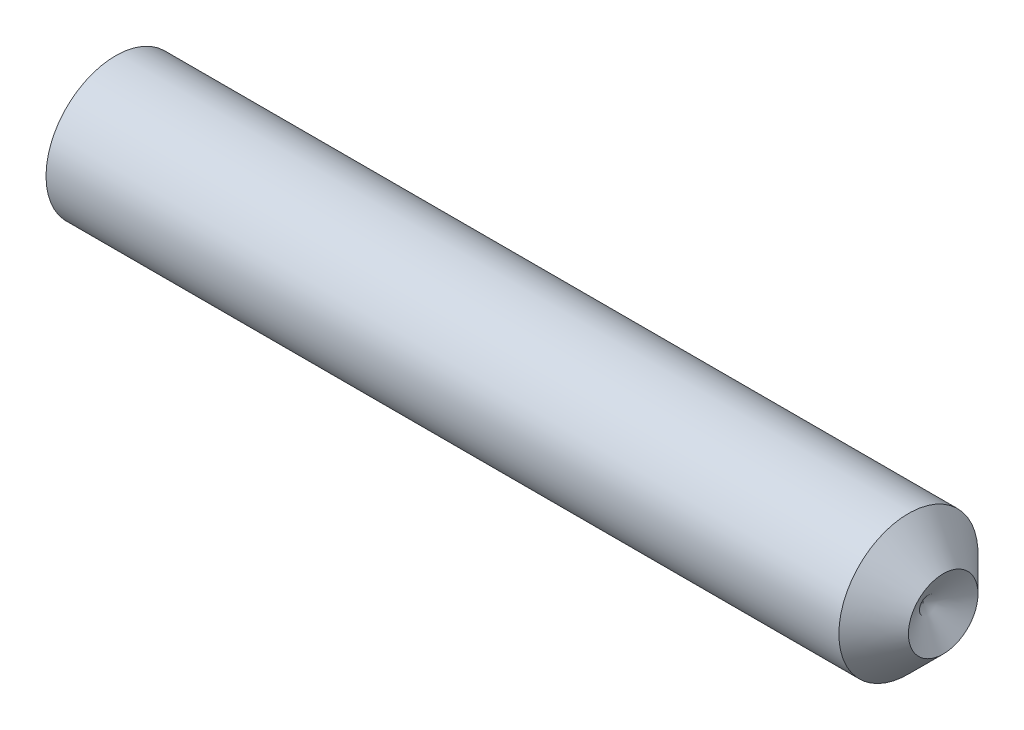
SolidWorks part; units mm, degrees
revolve "BaseBody" add sketch "BodySke" angle 360 about L5
sketch "BodySke" plane through (0, 0, 0) normal (0, 0, 1) x (1, 0, 0)
  line L0 (0, 0) -> (0, 2.055)
  line L1 (0, 2.055) -> (0.2569, 2.5)
  line L2 (0.2569, 2.5) -> (28.75, 2.5)
  line L3 (28.75, 2.5) -> (30, 1.25)
  line L4 (29.2783, 0) -> (0, 0)
  line L5 (-12.7, 0) -> (88.9, 0) construction
  line L6 (29.2783, 0) -> (30, 1.25)
  line L7 (30, 1.25) -> (30, 10.775) construction
  line L8 (0, -2.055) -> (0.2569, -2.5) construction
  line L9 (29.2783, 0) -> (30, -1.25) construction
  line L10 (28.75, -2.5) -> (30, -1.25) construction
  line L11 (0.4, 15.875) -> (0.4, -3.175) construction
  dimension "Diameter" = 5
  dimension "Drive_ch_ang" = 60
  dimension "Minor_dia" = 4.11
  dimension "Cup_ang" = 120
  dimension "Cup_dia" = 2.5
  dimension "Cup_nose_ang" = 45
  dimension "Advance" = 0.8
cosmetic thread "ThreadCosmetic" parameters "Thread_minor"=4.11
ref_plane "Plane1" through (0, 0, 0) normal (0, 0, 1) x (1, 0, 0)
ref_plane "Plane2" through (0, 0, 0) normal (0, 1, 0) x (1, 0, 0)
ref_plane "Plane3" through (0, 0, 0) normal (1, 0, 0) x (0, 0, -1)
sketch "Sketch2" plane through (0, 0, 0) normal (-1, 0, 0) x (0, 0, 1)
  line L0 (0.7217, 1.25) -> (-0.7217, 1.25)
  line L1 (-0.7217, 1.25) -> (-1.4434, 0)
  line L2 (0.7217, 1.25) -> (1.4434, 0)
  line L3 (0.7217, -1.25) -> (1.4434, 0)
  line L4 (0.7217, -1.25) -> (-0.7217, -1.25)
  line L5 (-0.7217, -1.25) -> (-1.4434, 0)
  dimension "Hex_size" = 2.5
  dimension "D2" = 1.25
  dimension "D3" = 1.25
extrude "Hex" cut sketch "Sketch2" against normal blind 2
sketch "ThdSchSke" plane through (0, 0, 0) normal (0, 0, 1) x (1, 0, 0)
  line L0 (0.2569, -2.055) -> (-0.0547, -2.5)
  line L1 (0.2569, -2.055) -> (0.5685, -2.5)
  line L2 (0.5685, -2.5) -> (0.5685, -3.125)
  line L3 (-3.175, 0) -> (5.1513, 0) construction
  line L4 (0.2569, 2.5) -> (0.2569, -2.5) construction
  line L5 (0.5685, -3.125) -> (-0.0547, -3.125)
  line L6 (-0.0547, -3.125) -> (-0.0547, -2.5)
  dimension "Thread_minor" = 4.11
  dimension "Diameter" = 5
revolve "ThreadSchematic" [suppressed] cut sketch "ThdSchSke" angle 360 about L3
pattern_linear "ThdSchPat" [suppressed]
equation "\"D2@Sketch2\" = \"Hex_size@Sketch2\" / 2"
equation "\"D3@Sketch2\" = \"Hex_size@Sketch2\" / 2"
equation "\"Thread_minor@ThreadCosmetic\" = \"Minor_dia@BodySke\""
equation "\"Thread_minor@ThdSchSke\" = \"Thread_minor@ThreadCosmetic\""
equation "\"Diameter@ThdSchSke\" = \"Diameter@BodySke\""
equation "\"Overcut@ThdSchSke\" = \"Diameter@BodySke\" * 1.25"
equation "\"Num_threads@ThdSchPat\" = int( (\"Length@BodySke\" - ( ( ( \"Diameter@BodySke\" - \"Minor_dia@BodySke\" ) * 0.5 ) / tan( \"Drive_ch_ang@BodySke\" * 0.017453292 ) ) - ( ( ( \"Diameter@BodySke\" - \"Cup_dia@BodySke\" ) * 0.5 ) * tan( \"Cup_nose_ang@BodySke\" * 0.017453292 ) ) ) / \"Advance@BodySke\" + 0.999 )  + 1"
equation "\"Advance@ThdSchPat\" = (\"Length@BodySke\" - ( ( ( \"Diameter@BodySke\" - \"Minor_dia@BodySke\" ) * 0.5 ) / tan( \"Drive_ch_ang@BodySke\" * 0.017453292 ) ) - ( ( ( \"Diameter@BodySke\" - \"Cup_dia@BodySke\" ) * 0.5 ) * tan( \"Cup_nose_ang@BodySke\" * 0.017453292 ) ) ) /  (\"Num_threads@ThdSchPat\" - 1) 'relax it"
equation "' \"Num_threads@ThdSchPat\" = \"Num_threads@ThdSchPat\" - sgn( \"Num_threads@ThdSchPat\" - 1) '---chamfered tips only---"
